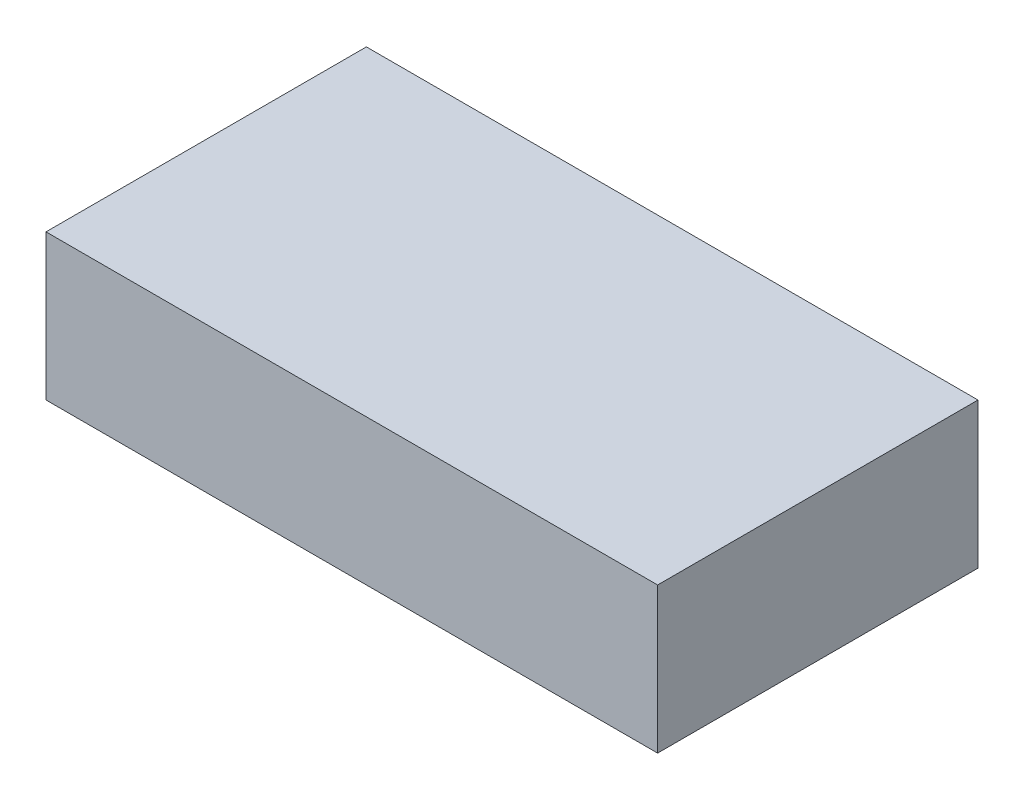
SolidWorks part; units mm, degrees
ref_plane "Ebene vorne" through (0, 0, 0) normal (0, 0, 1) x (1, 0, 0)
ref_plane "Ebene oben" through (0, 0, 0) normal (0, 1, 0) x (1, 0, 0)
ref_plane "Ebene rechts" through (0, 0, 0) normal (1, 0, 0) x (0, 0, -1)
sketch "Skizze1" plane through (0, 0, 0) normal (0, 1, 0) x (1, 0, 0)
  line L0 (0, 0) -> (105, 0)
  line L1 (-55, 0) -> (55, 0) construction
  line L2 (105, 0) -> (105, 55)
  line L3 (105, 55) -> (0, 55)
  line L4 (0, -55) -> (0, 55) construction
  line L5 (0, 55) -> (0, 0)
  dimension "D1" = 105
  dimension "D2" = 55
extrude "Aufsatz-Linear austragen1" add sketch "Skizze1" along normal blind 25
